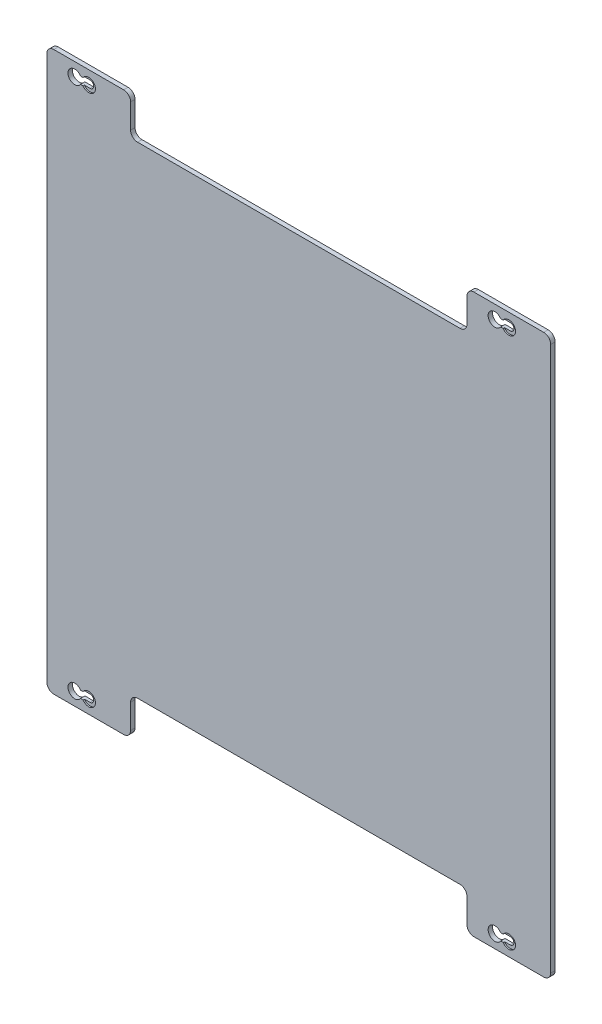
SolidWorks part; units mm, degrees
ref_plane "Front Plane" through (0, 0, 0) normal (0, 0, 1) x (1, 0, 0)
ref_plane "Top Plane" through (0, 0, 0) normal (0, 1, 0) x (1, 0, 0)
ref_plane "Right Plane" through (0, 0, 0) normal (1, 0, 0) x (0, 0, -1)
sketch "Model" plane through (0, 0, 0) normal (0, 0, 1) x (1, 0, 0)
  line L0 (175.5, 200) -> (125.5, 200)
  line L1 (144.6008, 187.9103) -> (150.5, 187.9103)
  line L2 (-175.5, 200) -> (-125.5, 200)
  line L3 (-115.5, 172.5) -> (115.5, 172.5)
  line L4 (-120.5, 177.5) -> (-120.5, 195)
  line L5 (150.5, 193.0897) -> (144.6008, 193.0897)
  line L6 (150.5, -187.9103) -> (144.6008, -187.9103)
  line L7 (-180.5, -195) -> (-180.5, 195)
  line L8 (-120.5, -177.5) -> (-120.5, -195)
  line L9 (-175.5, -200) -> (-125.5, -200)
  line L10 (-115.5, -172.5) -> (115.5, -172.5)
  line L11 (144.6008, -193.0897) -> (150.5, -193.0897)
  line L12 (-150.5, -187.9103) -> (-156.3992, -187.9103)
  line L13 (-156.3992, -193.0897) -> (-150.5, -193.0897)
  line L14 (180.5, 0) -> (-180.5, 0) construction
  line L15 (120.5, 177.5) -> (120.5, 195)
  line L16 (120.5, -177.5) -> (120.5, -195)
  line L17 (175.5, -200) -> (125.5, -200)
  line L18 (0, 172.5) -> (0, -220.1909) construction
  line L23 (180.5, 195) -> (180.5, -195)
  line L1211 (-150.5, 193.0897) -> (-156.3992, 193.0897)
  line L1300 (-156.3992, 187.9103) -> (-150.5, 187.9103)
  arc A0 (120.5, -195) -> (125.5, -200) centre (125.5, -195) ccw
  arc A1 (175.5, -200) -> (180.5, -195) centre (175.5, -195) ccw
  arc A2 (180.5, 195) -> (175.5, 200) centre (175.5, 195) ccw
  arc A3 (120.5, 195) -> (125.5, 200) centre (125.5, 195) cw
  arc A4 (120.5, 177.5) -> (115.5, 172.5) centre (115.5, 177.5) cw
  arc A5 (-120.5, 177.5) -> (-115.5, 172.5) centre (-115.5, 177.5) ccw
  arc A6 (-125.5, -200) -> (-120.5, -195) centre (-125.5, -195) ccw
  arc A7 (-115.5, -172.5) -> (-120.5, -177.5) centre (-115.5, -177.5) ccw
  arc A8 (-180.5, -195) -> (-175.5, -200) centre (-175.5, -195) ccw
  arc A9 (-120.5, 195) -> (-125.5, 200) centre (-125.5, 195) ccw
  arc A10 (-175.5, 200) -> (-180.5, 195) centre (-175.5, 195) ccw
  arc A11 (-150.5, 187.9103) -> (-150.5, 193.0897) centre (-150.5, 190.5) ccw
  arc A12 (120.5, -177.5) -> (115.5, -172.5) centre (115.5, -177.5) ccw
  arc A13 (144.6008, 193.0897) -> (144.6008, 187.9103) centre (140.5, 190.5) ccw
  arc A14 (150.5, 187.9103) -> (150.5, 193.0897) centre (150.5, 190.5) ccw
  arc A15 (146.3992, 187.9103) -> (146.3992, 193.0897) centre (150.5, 190.5) ccw construction
  arc A16 (144.6008, -187.9103) -> (144.6008, -193.0897) centre (140.5, -190.5) ccw
  arc A17 (146.3992, -193.0897) -> (146.3992, -187.9103) centre (150.5, -190.5) ccw construction
  arc A18 (150.5, -193.0897) -> (150.5, -187.9103) centre (150.5, -190.5) ccw
  arc A19 (-154.6008, -193.0897) -> (-154.6008, -187.9103) centre (-150.5, -190.5) ccw construction
  arc A20 (-150.5, -193.0897) -> (-150.5, -187.9103) centre (-150.5, -190.5) ccw
  arc A21 (-156.3992, -187.9103) -> (-156.3992, -193.0897) centre (-160.5, -190.5) ccw
  arc A31 (-154.6008, 187.9103) -> (-154.6008, 193.0897) centre (-150.5, 190.5) ccw construction
  arc A32 (-156.3992, 193.0897) -> (-156.3992, 187.9103) centre (-160.5, 190.5) ccw
  dimension "D1" = 345
  dimension "D11" = 5
  dimension "D12" = 4.85
  dimension "D13" = 4.85
  dimension "D17" = 5
  dimension "D18" = 5
  dimension "D19" = 5
  dimension "D20" = 5
  dimension "D21" = 5
  dimension "D22" = 5
  dimension "D23" = 5
  dimension "D24" = 5
  dimension "D25" = 5
  dimension "D26" = 5
  dimension "D27" = 5
  dimension "D31" = 160.5
  dimension "D28" = 190.5
  dimension "D2" = 172.5
  dimension "D3" = 361
  dimension "D4" = 180.5
  dimension "D5" = 60
  dimension "D6" = 60
  dimension "D7" = 400
  dimension "D8" = 60
  dimension "D14" = 10
  dimension "D15" = 60
  dimension "D30" = 5.1793
  dimension "D32" = 2
  dimension "D33" = 2
extrude "Boss-Extrude1" add sketch "Model" along normal blind 3.175
sketch "Sketch2" plane through (0, 0, 3.175) normal (0, 0, 1) x (1, 0, 0)
  circle A0 centre (-150.5, 190.5) radius 4.8
  circle A1 centre (150.5, 190.5) radius 4.8
  circle A2 centre (150.5, -190.5) radius 4.8
  circle A3 centre (-150.5, -190.5) radius 4.8
  dimension "D1" = 9.6
extrude "Cut-Extrude1" cut sketch "Sketch2" against normal blind 1
sketch "Sketch3" plane through (0, 0, 3.175) normal (0, 0, 1) x (1, 0, 0)
  line L0 (-15, 162.5) -> (15, 162.5)
  line L1 (-150, -150) -> (150, -150) construction
  line L2 (-150, -150) -> (-150, 150) construction
  line L3 (-150, 150) -> (150, 150) construction
  line L4 (150, -150) -> (150, 150) construction
  line L5 (-150, -150) -> (150, 150) construction
  line L6 (-150, 150) -> (150, -150) construction
  line L7 (-15, 172.025) -> (15, 172.025)
  line L8 (35, 172.025) -> (65, 172.025)
  line L9 (35, 162.5) -> (65, 162.5)
  line L10 (85, 172.025) -> (115, 172.025)
  line L11 (85, 162.5) -> (115, 162.5)
  line L14 (-65, 172.025) -> (-35, 172.025)
  line L15 (-65, 162.5) -> (-35, 162.5)
  line L16 (-115, 172.025) -> (-85, 172.025)
  line L17 (-115, 162.5) -> (-85, 162.5)
  line L20 (-180.5, 0) -> (180.5, 0) construction
  line L21 (-180.5, 195) -> (-180.5, -195) construction
  line L22 (180.5, -195) -> (180.5, 195) construction
  line L25 (-115, -162.5) -> (-85, -162.5)
  line L26 (-115, -172.025) -> (-85, -172.025)
  line L27 (-65, -162.5) -> (-35, -162.5)
  line L28 (-65, -172.025) -> (-35, -172.025)
  line L31 (85, -162.5) -> (115, -162.5)
  line L32 (85, -172.025) -> (115, -172.025)
  line L33 (35, -162.5) -> (65, -162.5)
  line L34 (35, -172.025) -> (65, -172.025)
  line L35 (-15, -172.025) -> (15, -172.025)
  line L36 (-15, -162.5) -> (15, -162.5)
  arc A0 (15, 172.025) -> (15, 162.5) centre (15, 167.2625) cw
  arc A1 (-15, 162.5) -> (-15, 172.025) centre (-15, 167.2625) cw
  arc A2 (35, 162.5) -> (35, 172.025) centre (35, 167.2625) cw
  arc A3 (65, 172.025) -> (65, 162.5) centre (65, 167.2625) cw
  arc A4 (85, 162.5) -> (85, 172.025) centre (85, 167.2625) cw
  arc A5 (115, 172.025) -> (115, 162.5) centre (115, 167.2625) cw
  arc A8 (-65, 162.5) -> (-65, 172.025) centre (-65, 167.2625) cw
  arc A9 (-35, 172.025) -> (-35, 162.5) centre (-35, 167.2625) cw
  arc A10 (-115, 162.5) -> (-115, 172.025) centre (-115, 167.2625) cw
  arc A11 (-85, 172.025) -> (-85, 162.5) centre (-85, 167.2625) cw
  arc A16 (-85, -172.025) -> (-85, -162.5) centre (-85, -167.2625) ccw
  arc A17 (-115, -162.5) -> (-115, -172.025) centre (-115, -167.2625) ccw
  arc A18 (-35, -172.025) -> (-35, -162.5) centre (-35, -167.2625) ccw
  arc A19 (-65, -162.5) -> (-65, -172.025) centre (-65, -167.2625) ccw
  arc A22 (115, -172.025) -> (115, -162.5) centre (115, -167.2625) ccw
  arc A23 (85, -162.5) -> (85, -172.025) centre (85, -167.2625) ccw
  arc A24 (65, -172.025) -> (65, -162.5) centre (65, -167.2625) ccw
  arc A25 (35, -162.5) -> (35, -172.025) centre (35, -167.2625) ccw
  arc A26 (-15, -162.5) -> (-15, -172.025) centre (-15, -167.2625) ccw
  arc A27 (15, -172.025) -> (15, -162.5) centre (15, -167.2625) ccw
  point P0 (0, 0)
  point P12 (0, 162.5)
  dimension "D3" = 4.7625
  dimension "D4" = 30
  dimension "D1" = 300
  dimension "D2" = 300
  dimension "D5" = 25
  dimension "D6" = 3
  dimension "D7" = 3
extrude "Cut-Extrude2" [suppressed] cut sketch "Sketch3" against normal up to surface (3.175 mm away)
equation "\"D2@Model\"=\"D1@Model\"/2"
